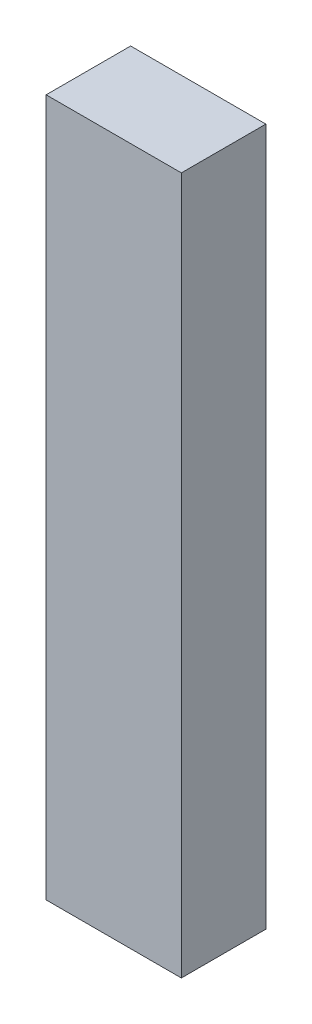
SolidWorks part; units mm, degrees
ref_plane "前视基准面" through (0, 0, 0) normal (0, 0, 1) x (1, 0, 0)
ref_plane "上视基准面" through (0, 0, 0) normal (0, 1, 0) x (1, 0, 0)
ref_plane "右视基准面" through (0, 0, 0) normal (1, 0, 0) x (0, 0, -1)
other "Configuration Table"
sketch "草图1" plane through (0, 0, 0) normal (0, 0, 1) x (1, 0, 0)
  line L1 (-160, 825) -> (160, 825)
  line L2 (-160, 825) -> (-160, -825)
  line L3 (-160, -825) -> (160, -825)
  line L4 (160, 825) -> (160, -825)
  line L5 (-160, 825) -> (160, -825) construction
  line L6 (-160, -825) -> (160, 825) construction
  point P0 (0, 0)
extrude "凸台-拉伸1" add sketch "草图1" along normal blind 200
